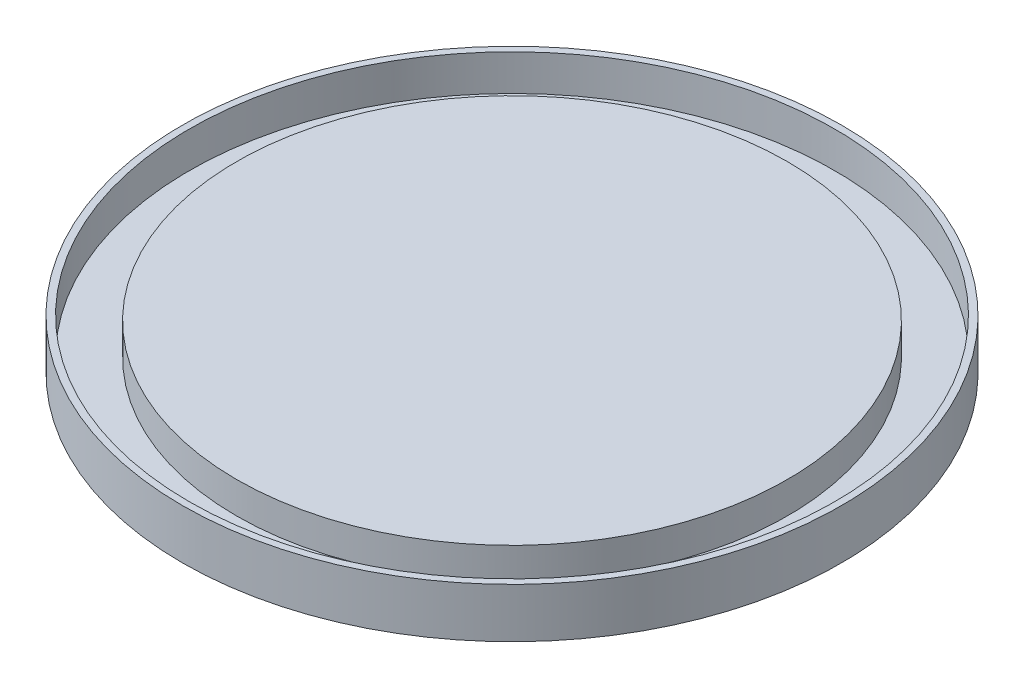
SolidWorks part; units mm, degrees
ref_plane "정면" through (0, 0, 0) normal (0, 0, 1) x (1, 0, 0)
ref_plane "윗면" through (0, 0, 0) normal (0, 1, 0) x (1, 0, 0)
ref_plane "우측면" through (0, 0, 0) normal (1, 0, 0) x (0, 0, -1)
sketch "스케치1" plane through (0, 0, 0) normal (0, 1, 0) x (1, 0, 0)
  circle A0 centre (0, 0) radius 71.5
  circle A1 centre (0, 0) radius 73
  dimension "D1" = 146
  dimension "D2" = 143
extrude "보스-돌출1" add sketch "스케치1" along normal blind 11
sketch "스케치2" plane through (0, 0, 0) normal (0, 1, 0) x (1, 0, 0)
  circle A0 centre (0, 0) radius 61
  circle A1 centre (0, 0) radius 71.5
  dimension "D1" = 143
  dimension "D2" = 122
extrude "보스-돌출2" add sketch "스케치2" along normal blind 3
sketch "스케치3" plane through (0, 0, 0) normal (0, 1, 0) x (1, 0, 0)
  circle A0 centre (0, 0) radius 59.5
  circle A1 centre (0, 0) radius 61
  dimension "D1" = 122
  dimension "D2" = 119
extrude "보스-돌출3" add sketch "스케치3" along normal blind 10
sketch "스케치4" plane through (0, 0, 0) normal (0, 1, 0) x (1, 0, 0)
  circle A0 centre (0, 0) radius 59.5
  dimension "D1" = 119
extrude "보스-돌출4" add sketch "스케치4" along normal blind 3 from offset 7
sketch "스케치6" plane through (0, 7, 0) normal (0, -1, 0) x (1, 0, 0)
  line L0 (-1.8043, 9.8359) -> (-10.7356, 58.5235)
  line L1 (-5.5941, 59.2364) -> (-0.9402, 9.9557)
  line L2 (-48.5032, -34.4628) -> (-8.1518, -5.7921)
  line L3 (-7.616, -6.4805) -> (-45.315, -38.559)
  line L4 (9.4203, -3.3554) -> (56.0506, -19.9645)
  line L5 (9.092, -4.1636) -> (54.0973, -24.7736)
  circle A0 centre (0, 0) radius 59.5 construction
  arc A1 (-48.5032, -34.4628) -> (-45.315, -38.559) centre (0, 0) ccw
  arc A2 (-1.8043, 9.8359) -> (-8.1518, -5.7921) centre (0, 0) ccw
  arc A3 (-5.5941, 59.2364) -> (-10.7356, 58.5235) centre (0, 0) ccw
  arc A4 (54.0973, -24.7736) -> (56.0506, -19.9645) centre (0, 0) ccw
  arc A5 (9.4203, -3.3554) -> (-0.9402, 9.9557) centre (0, 0) ccw
  arc A6 (-7.616, -6.4805) -> (9.092, -4.1636) centre (0, 0) ccw
  dimension "D4" = 20
  dimension "D1" = 5
  dimension "D2" = 5
  dimension "D3" = 5
  dimension "D5" = 115
  dimension "D6" = 115
extrude "보스-돌출5" add sketch "스케치6" along normal blind 7
